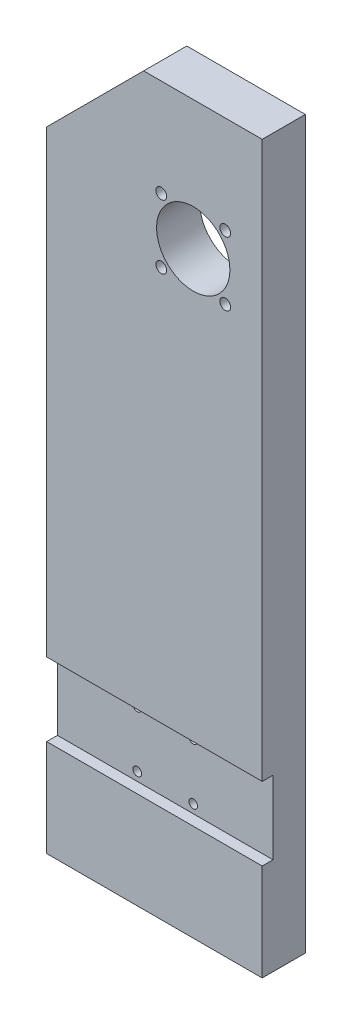
SolidWorks part; units mm, degrees
ref_plane "Front Plane" through (0, 0, 0) normal (0, 0, 1) x (1, 0, 0)
ref_plane "Top Plane" through (0, 0, 0) normal (0, 1, 0) x (1, 0, 0)
ref_plane "Right Plane" through (0, 0, 0) normal (1, 0, 0) x (0, 0, -1)
sketch "Sketch1" plane through (0, 0, 0) normal (0, 0, 1) x (1, 0, 0)
  line L0 (65.7045, 560.5004) -> (50.8553, 575.3496) construction
  line L1 (65.7045, 560.5004) -> (44.7045, 560.5004) construction
  line L2 (65.7045, 560.5004) -> (65.7045, 581.5004) construction
  line L3 (47.7045, 545.8558) -> (47.7045, 439.2537) construction
  line L4 (7.7288, 345.5004) -> (63.5732, 345.5004) construction
  line L5 (97.7045, 283.5004) -> (-2.2955, 283.5004)
  line L6 (97.7045, 283.5004) -> (97.7045, 620.5004)
  line L7 (97.7045, 620.5004) -> (-2.2955, 620.5004)
  line L8 (-2.2955, 283.5004) -> (-2.2955, 620.5004)
  line L9 (97.7045, 283.5004) -> (-2.2955, 620.5004) construction
  line L10 (97.7045, 620.5004) -> (-2.2955, 283.5004) construction
  circle A0 centre (65.7045, 560.5004) radius 17
  circle A1 centre (65.7045, 560.5004) radius 21 construction
  circle A2 centre (80.5538, 575.3496) radius 2.5
  circle A3 centre (80.5538, 545.6511) radius 2.5
  circle A4 centre (50.8553, 545.6511) radius 2.5
  circle A5 centre (50.8553, 575.3496) radius 2.5
  circle A6 centre (34.7045, 358.5004) radius 2
  circle A7 centre (60.7045, 358.5004) radius 2
  circle A8 centre (60.7045, 332.5004) radius 2
  circle A9 centre (34.7045, 332.5004) radius 2
  point P5 (50.8553, 575.3496)
  point P6 (80.5538, 575.3496)
  point P7 (80.5538, 545.6511)
  point P8 (50.8553, 545.6511)
  point P19 (47.7045, 452.0004)
  dimension "D2" = 5
  dimension "D3" = 34
  dimension "D4" = 42
  dimension "D10" = 4
  dimension "D1" = 45
  dimension "D5" = 337
  dimension "D6" = 100
  dimension "D7" = 60
  dimension "D8" = 13
  dimension "D9" = 13
  dimension "D11" = 62
  dimension "D12" = 32
extrude "Boss-Extrude1" add sketch "Sketch1" along normal blind 20
chamfer "Chamfer1" distance 45 angle 45 1 edges at (-2.2955, 620.5004, 10)
sketch "Sketch2" plane through (0, 0, 20) normal (0, 0, 1) x (1, 0, 0)
  line L0 (60.7045, 358.5004) -> (34.7045, 332.5004) construction
  line L1 (34.7045, 358.5004) -> (60.7045, 332.5004) construction
  line L3 (97.7045, 328.5004) -> (-2.2955, 328.5004)
  line L4 (97.7045, 328.5004) -> (97.7045, 362.5004)
  line L5 (97.7045, 362.5004) -> (-2.2955, 362.5004)
  line L6 (-2.2955, 328.5004) -> (-2.2955, 362.5004)
  line L7 (97.7045, 328.5004) -> (-2.2955, 362.5004) construction
  line L8 (97.7045, 362.5004) -> (-2.2955, 328.5004) construction
  point P8 (47.7045, 345.5004)
  point P9 (47.7045, 345.5004)
  dimension "D1" = 100
  dimension "D2" = 34
extrude "Cut-Extrude1" cut sketch "Sketch2" against normal blind 5
sketch "Sketch3" plane through (0, 283.5004, 0) normal (0, -1, 0) x (1, 0, 0)
  line L0 (-2.2955, 10) -> (97.7045, 10) construction
  line L1 (-2.2955, 20) -> (-2.2955, 0) construction
  line L2 (97.7045, 20) -> (97.7045, 0) construction
  line L3 (47.7045, 20) -> (47.7045, 0) construction
  line L4 (-2.2955, 20) -> (97.7045, 20) construction
  line L5 (-2.2955, 0) -> (97.7045, 0) construction
  point P12 (67.7045, 10)
  point P13 (87.7045, 10)
  point P14 (7.7045, 10)
  point P15 (27.7045, 10)
  dimension "D1" = 20
  dimension "D2" = 40
hole_wizard "M4 Tapped Hole1" positions "3DSketch1" profile "Sketch4" tap size "M4" standard "ISO"
sketch3d "3DSketch1"
  point P0 (7.7045, 283.5004, 10)
  point P10 (27.7045, 283.5004, 10)
  point P13 (67.7045, 283.5004, 10)
  point P16 (87.7045, 283.5004, 10)
sketch "Sketch4" plane through (7.7045, 283.5004, 10) normal (1, 0, 0) x (0, 0, -1)
  line L0 (0, 0) -> (0, 17.0914)
  line L1 (0, 17.0914) -> (1.65, 16.1)
  line L2 (1.65, 16.1) -> (1.65, 0)
  line L5 (1.65, 0) -> (0, 0)
  line L10 (0, 17.0914) -> (-1.65, 16.1) construction
  line L11 (0, -6.35) -> (0, 107.95) construction
  dimension "Tap Drill Dia." = 3.3
  dimension "Tap Drill Depth" = 16.1
  dimension "Drill Angle" = 118
